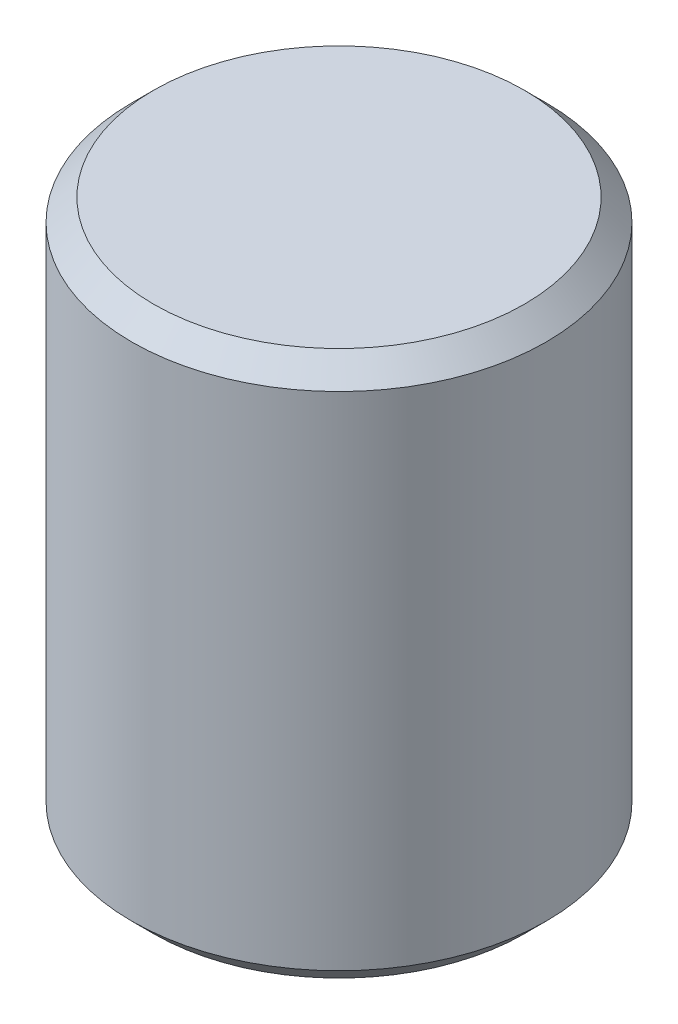
SolidWorks part; units mm, degrees
material "1060 Alloy"
ref_plane "Front" through (0, 0, 0) normal (0, 0, 1) x (1, 0, 0)
ref_plane "Top" through (0, 0, 0) normal (0, 1, 0) x (1, 0, 0)
ref_plane "Right" through (0, 0, 0) normal (1, 0, 0) x (0, 0, -1)
sketch "Sketch1" plane through (0, 0, 0) normal (0, 1, 0) x (1, 0, 0)
  circle A0 centre (0, 0) radius 9.5
  dimension "D1" = 19
extrude "Boss-Extrude1" add sketch "Sketch1" along normal blind 25
chamfer "Chamfer1" distance 1 angle 45 2 edges at (0, 0, 9.5) (0, 25, 9.5)
